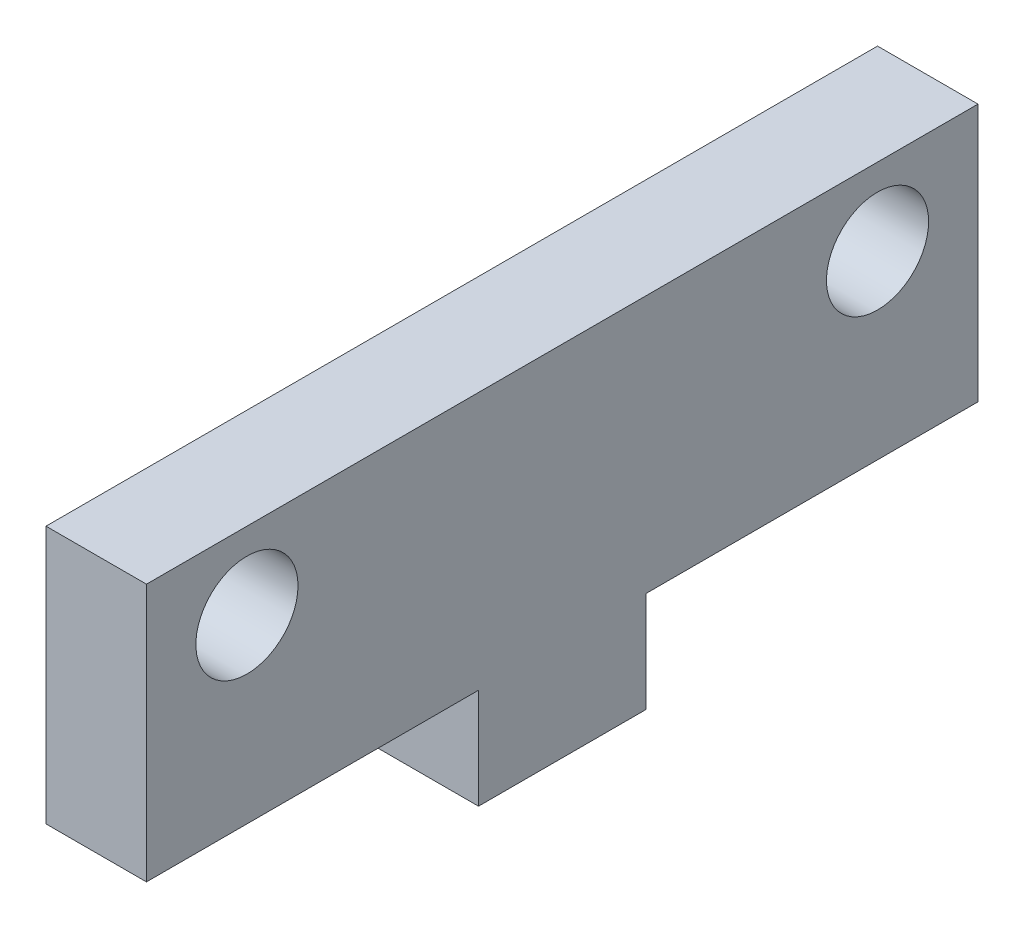
SolidWorks part; units mm, degrees
ref_plane "Front Plane" through (0, 0, 0) normal (0, 0, 1) x (1, 0, 0)
ref_plane "Top Plane" through (0, 0, 0) normal (0, 1, 0) x (1, 0, 0)
ref_plane "Right Plane" through (0, 0, 0) normal (1, 0, 0) x (0, 0, -1)
sketch "Sketch1" plane through (0, 0, 0) normal (1, 0, 0) x (0, 0, -1)
  line L0 (0, 0) -> (-9.915, 0)
  line L1 (-24.83, 0) -> (-24.83, 7.7)
  line L2 (-24.83, 7.7) -> (0, 7.7)
  line L3 (0, 7.7) -> (0, 0)
  line L4 (-14.915, 0) -> (-14.915, -3)
  line L5 (-14.915, -3) -> (-9.915, -3)
  line L6 (-9.915, -3) -> (-9.915, 0)
  line L7 (-14.915, 0) -> (-24.83, 0)
  circle A0 centre (-21.83, 5.4) radius 1.525
  circle A1 centre (-3, 5.4) radius 1.525
  point P13 (0, 0)
  dimension "D1" = 3.05
  dimension "D2" = 2.3
  dimension "D3" = 7.7
  dimension "D4" = 3
  dimension "D5" = 18.83
  dimension "D6" = 3
  dimension "D7" = 3
  dimension "D8" = 5
extrude "Boss-Extrude1" add sketch "Sketch1" along normal blind 3
